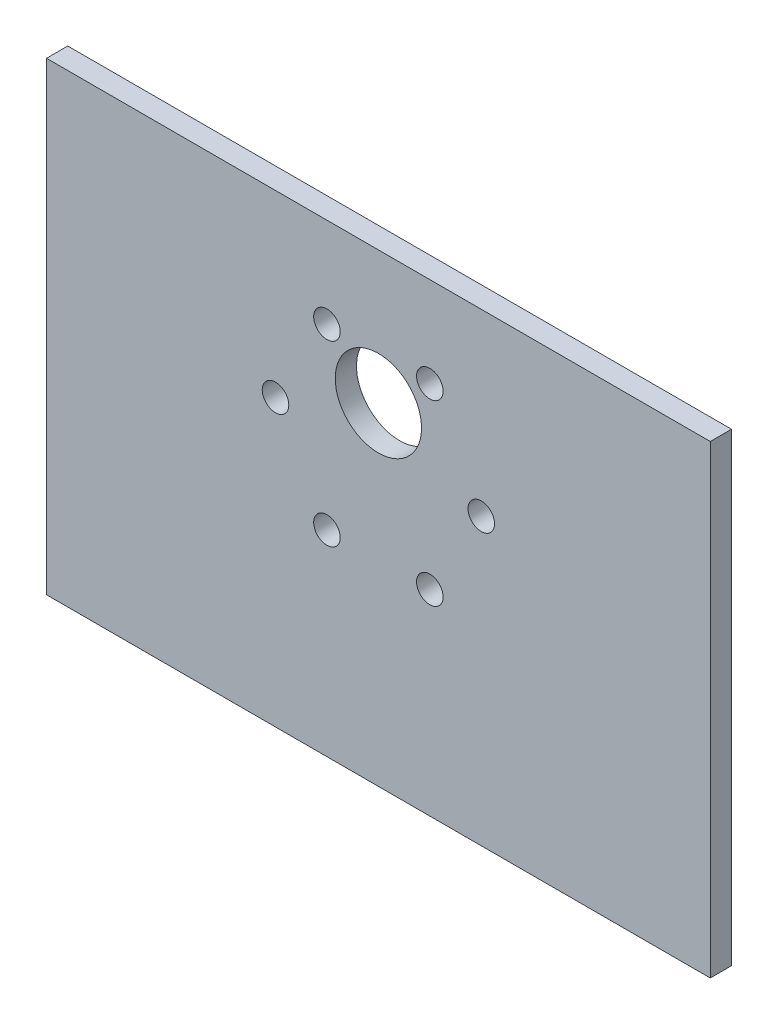
SolidWorks part; units mm, degrees
ref_plane "Спереди" through (0, 0, 0) normal (0, 0, 1) x (1, 0, 0)
ref_plane "Сверху" through (0, 0, 0) normal (0, 1, 0) x (1, 0, 0)
ref_plane "Справа" through (0, 0, 0) normal (1, 0, 0) x (0, 0, -1)
other "Configuration Table"
sketch "Эскиз1" plane through (0, 0, 0) normal (0, 0, 1) x (1, 0, 0)
  line L1 (-50, 27) -> (50, 27)
  line L2 (-50, 27) -> (-50, -43)
  line L3 (-50, -43) -> (50, -43)
  line L4 (50, 27) -> (50, -43)
  circle A0 centre (7.75, -13.4234) radius 2
  circle A1 centre (-7.75, -13.4234) radius 2
  circle A2 centre (-15.5, 0) radius 2
  circle A3 centre (-7.75, 13.4234) radius 2
  circle A4 centre (7.75, 13.4234) radius 2
  circle A5 centre (15.5, 0) radius 2
  circle A6 centre (0, 7) radius 6.5
  point P16 (0, 0)
  dimension "D1" = 6
  dimension "D2" = 100
  dimension "D3" = 70
  dimension "D4" = 50
  dimension "D5" = 20
extrude "Бобышка-Вытянуть2" add sketch "Эскиз1" along normal blind 3.2
